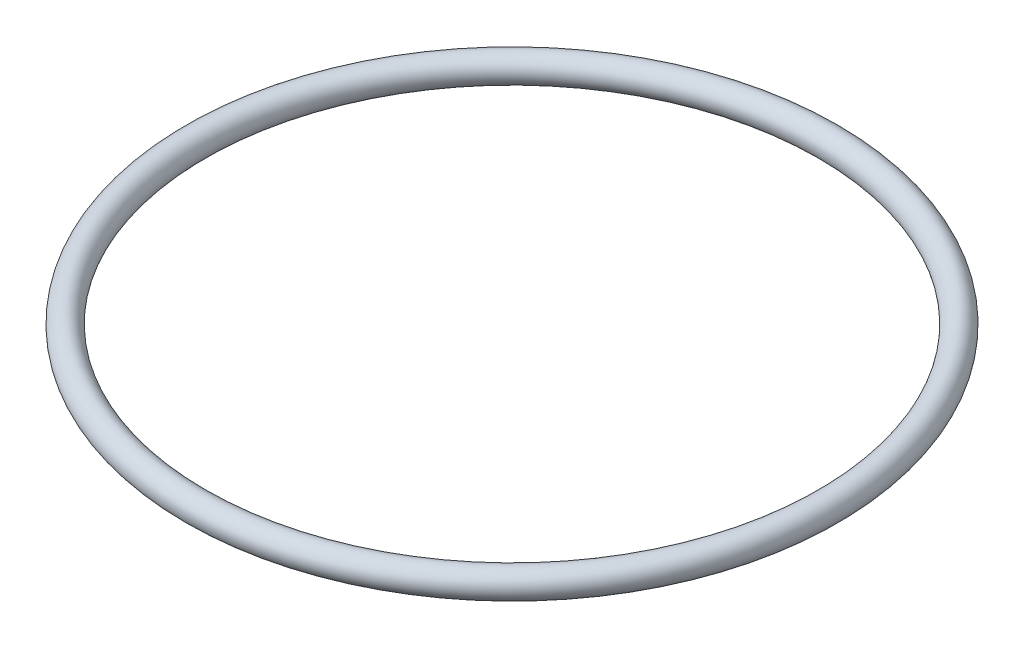
SolidWorks part; units mm, degrees
ref_plane "Front Plane" through (0, 0, 0) normal (0, 0, 1) x (1, 0, 0)
ref_plane "Top Plane" through (0, 0, 0) normal (0, 1, 0) x (1, 0, 0)
ref_plane "Right Plane" through (0, 0, 0) normal (1, 0, 0) x (0, 0, -1)
sketch "Sketch1" plane through (0, 0, 0) normal (0, 0, 1) x (1, 0, 0)
  line L0 (0, 0) -> (50000, 0) construction
  line L1 (0, 0) -> (0, 50000) construction
  circle A0 centre (30.5181, 0) radius 1.3081
  point P6 (29.21, 0)
  dimension "D1" = 2.6162
  dimension "D2" = 29.21
revolve "Revolve1" add sketch "Sketch1" angle 360 about L1
sketch "Sketch2" plane through (0, 0, 0) normal (0, 1, 0) x (1, 0, 0)
  circle A0 centre (0, 0) radius 31.8262
  circle A1 centre (0, 0) radius 31.8262 construction
